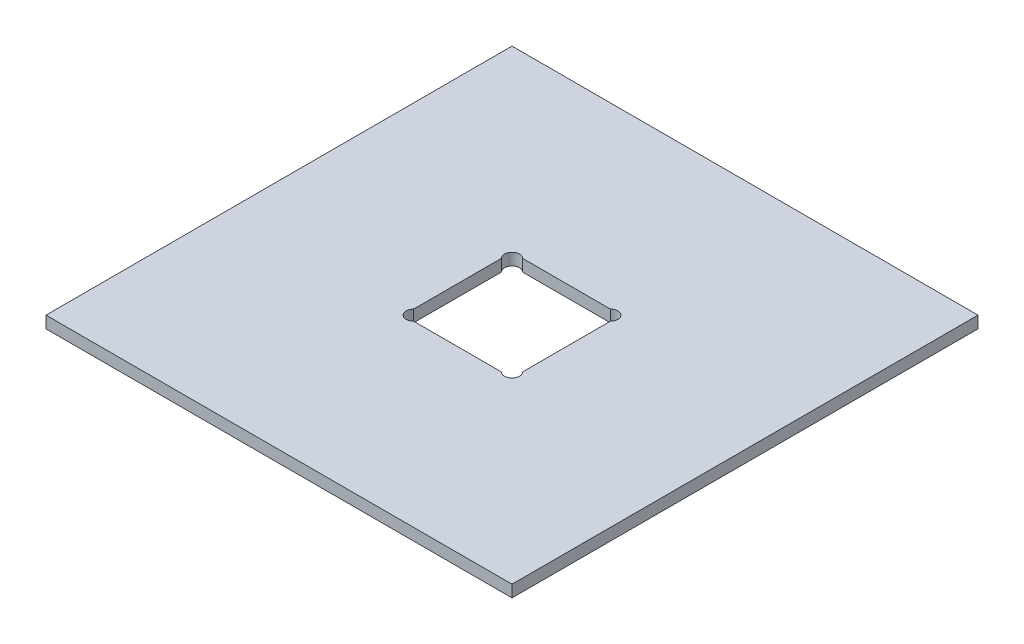
SolidWorks part; units mm, degrees
ref_plane "Front" through (0, 0, 0) normal (0, 0, 1) x (1, 0, 0)
ref_plane "Top" through (0, 0, 0) normal (0, 1, 0) x (1, 0, 0)
ref_plane "Right" through (0, 0, 0) normal (1, 0, 0) x (0, 0, -1)
sketch "草图1" plane through (0, 0, 0) normal (0, 1, 0) x (1, 0, 0)
  line L1 (-31.3206, -31.3206) -> (31.3206, -31.3206)
  line L2 (-31.3206, -31.3206) -> (-31.3206, 31.3206)
  line L3 (-31.3206, 31.3206) -> (31.3206, 31.3206)
  line L4 (31.3206, -31.3206) -> (31.3206, 31.3206)
  line L5 (-31.3206, -31.3206) -> (31.3206, 31.3206) construction
  line L6 (-31.3206, 31.3206) -> (31.3206, -31.3206) construction
  point P0 (0, 0)
  dimension "D1" = 45
extrude "凸台-拉伸1" add sketch "草图1" along normal blind 1.6
sketch "草图2" plane through (0, 1.6, 0) normal (0, 1, 0) x (1, 0, 0)
  line L0 (-5.9064, 7.3206) -> (5.9064, 7.3206)
  line L1 (7.3206, 5.9064) -> (7.3206, -5.9064)
  line L2 (5.9064, -7.3206) -> (-5.9064, -7.3206)
  line L3 (-7.3206, -5.9064) -> (-7.3206, 5.9064)
  line L4 (-7.3206, 7.3206) -> (7.3206, -7.3206) construction
  line L5 (7.3206, 7.3206) -> (-11.6062, -11.6062) construction
  line L8 (7.3206, -7.3206) -> (7.3206, 7.3206)
  line L9 (7.3206, 7.3206) -> (-7.3206, 7.3206)
  line L10 (-7.3206, 7.3206) -> (-7.3206, -7.3206)
  line L11 (-7.3206, -7.3206) -> (7.3206, -7.3206)
  line L12 (7.3206, -7.3206) -> (7.3206, 7.3206) construction
  line L13 (7.3206, 7.3206) -> (-7.3206, 7.3206) construction
  line L14 (-7.3206, 7.3206) -> (-7.3206, -7.3206) construction
  line L15 (-7.3206, -7.3206) -> (7.3206, -7.3206) construction
  circle A0 centre (-6.6135, 6.6135) radius 1 construction
  arc A1 (-5.9064, 7.3206) -> (-7.3206, 5.9064) centre (-6.6135, 6.6135) ccw
  arc A2 (7.3206, 5.9064) -> (5.9064, 7.3206) centre (6.6135, 6.6135) ccw
  arc A3 (5.9064, -7.3206) -> (7.3206, -5.9064) centre (6.6135, -6.6135) ccw
  arc A4 (-7.3206, -5.9064) -> (-5.9064, -7.3206) centre (-6.6135, -6.6135) ccw
  point P21 (0, 0)
  point P28 (0, 0)
  dimension "D2" = 2
  dimension "D1" = 24
  dimension "D3" = 4
  dimension "D4" = 4
extrude "切除-拉伸1" cut sketch "草图2" against normal blind 1.6
